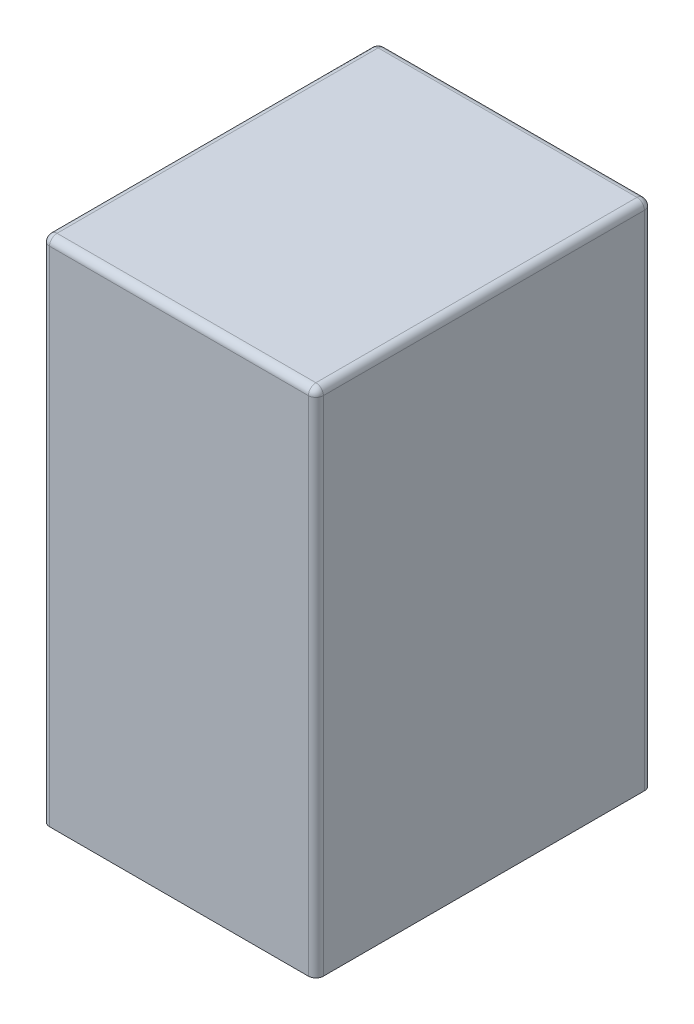
SolidWorks part; units mm, degrees
ref_plane "前视基准面" through (0, 0, 0) normal (0, 0, 1) x (1, 0, 0)
ref_plane "上视基准面" through (0, 0, 0) normal (0, 1, 0) x (1, 0, 0)
ref_plane "右视基准面" through (0, 0, 0) normal (1, 0, 0) x (0, 0, -1)
sketch "Sketch1" plane through (0, 0, 0) normal (0, 1, 0) x (1, 0, 0)
  line L0 (-55, 67.5) -> (55, 67.5)
  line L1 (-50, 62.5) -> (50, 62.5)
  line L2 (-50, 62.5) -> (-50, -62.5)
  line L3 (-50, -62.5) -> (50, -62.5)
  line L4 (50, 62.5) -> (50, -62.5)
  line L5 (-50, 62.5) -> (50, -62.5) construction
  line L6 (-50, -62.5) -> (50, 62.5) construction
  line L7 (55, 67.5) -> (55, -67.5)
  line L8 (-55, -67.5) -> (55, -67.5)
  line L9 (-55, 67.5) -> (-55, -67.5)
  point P0 (0, 0)
  dimension "D1" = 100
  dimension "D2" = 125
  dimension "D3" = 5
extrude "Boss-Extrude1" add sketch "Sketch1" along normal blind 200
sketch "Sketch2" plane through (0, 200, 0) normal (0, 1, 0) x (1, 0, 0)
  line L4 (-55, 67.5) -> (-55, -67.5)
  line L5 (-55, -67.5) -> (55, -67.5)
  line L6 (55, -67.5) -> (55, 67.5)
  line L7 (55, 67.5) -> (-55, 67.5)
  line L8 (-55, 67.5) -> (-55, -67.5)
  line L9 (-55, -67.5) -> (55, -67.5)
  line L10 (55, -67.5) -> (55, 67.5)
  line L11 (55, 67.5) -> (-55, 67.5)
  dimension "D1" = 0
extrude "Boss-Extrude2" add sketch "Sketch2" along normal blind 5
sketch "Sketch3" plane through (0, 0, 0) normal (0, -1, 0) x (1, 0, 0)
  line L0 (50, -62.5) -> (-50, -62.5) construction
  line L1 (50, 62.5) -> (50, -62.5) construction
  line L2 (-50, 62.5) -> (50, 62.5) construction
  line L3 (-50, -62.5) -> (-50, 62.5) construction
  line L4 (-55, 67.5) -> (-55, -67.5)
  line L5 (-55, -67.5) -> (55, -67.5)
  line L6 (55, -67.5) -> (55, 67.5)
  line L7 (55, 67.5) -> (-55, 67.5)
  line L8 (-55, 67.5) -> (-55, -67.5)
  line L9 (-55, -67.5) -> (55, -67.5)
  line L10 (55, -67.5) -> (55, 67.5)
  line L11 (55, 67.5) -> (-55, 67.5)
  line L12 (50, -62.5) -> (-50, -62.5)
  line L13 (50, 62.5) -> (50, -62.5)
  line L14 (-50, 62.5) -> (50, 62.5)
  line L15 (-50, -62.5) -> (-50, 62.5)
  line L16 (-52.5, 65) -> (52.5, 65)
  line L17 (52.5, 65) -> (52.5, -65)
  line L18 (52.5, -65) -> (-52.5, -65)
  line L19 (-52.5, -65) -> (-52.5, 65)
  circle A1 centre (0, 65) radius 1.45
  circle A2 centre (-52.5, 65) radius 1.45
  circle A3 centre (-52.5, -65) radius 1.45
  circle A4 centre (52.5, -65) radius 1.45
  circle A5 centre (52.5, 65) radius 1.45
  circle A6 centre (52.5, 0) radius 1.45
  circle A7 centre (-52.5, 0) radius 1.45
  circle A8 centre (0, -65) radius 1.45
  dimension "D2" = 2.5
  dimension "D1" = 0
extrude "Cut-Extrude1" cut sketch "Sketch3" against normal blind 12 contours L18 A8 | L18 A8 | L18 A4 L17 | L17 A4 L18 | L17 A6 | L17 A6 | L16 A5 L17 | L17 A5 L16 | L16 A1 | L16 A1 | L19 A2 L16 | L16 A2 L19 | L19 A7 | L19 A7 | L19 A3 L18 | L18 A3 L19
fillet "Fillet1" radius 3 8 edges at (55, 205, 0) (0, 205, 67.5) (-55, 205, 0) (0, 205, -67.5) (-55, 102.5, -67.5) (-55, 102.5, 67.5) (55, 102.5, 67.5) (55, 102.5, -67.5)
